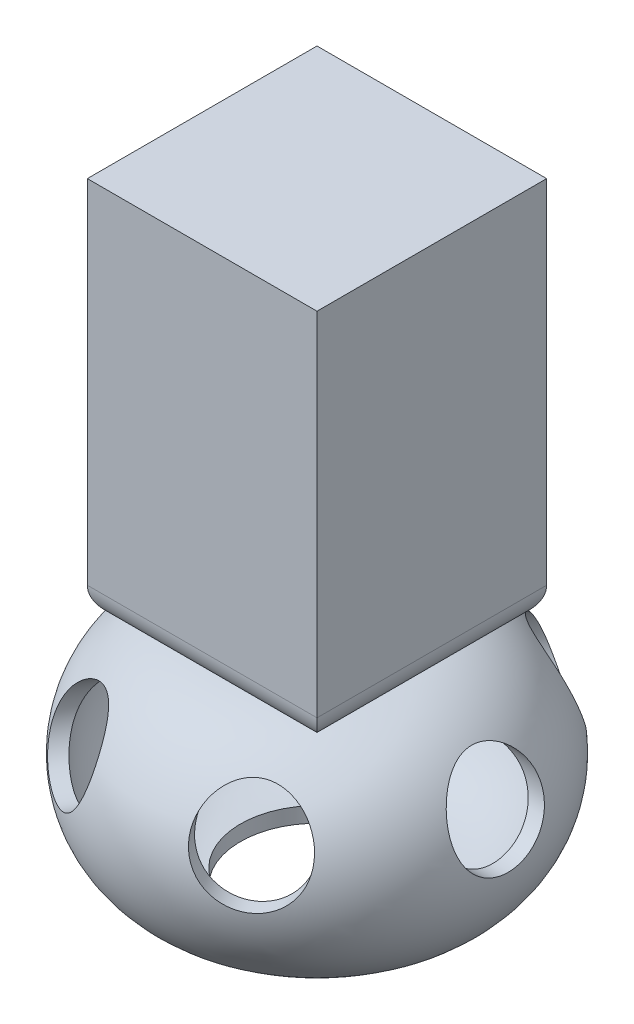
SolidWorks part; units mm, degrees
material "PLA"
ref_plane "Front Plane" through (0, 0, 0) normal (0, 0, 1) x (1, 0, 0)
ref_plane "Top Plane" through (0, 0, 0) normal (0, 1, 0) x (1, 0, 0)
ref_plane "Right Plane" through (0, 0, 0) normal (1, 0, 0) x (0, 0, -1)
sketch "Sketch1" plane through (0, 0, 0) normal (0, 1, 0) x (1, 0, 0)
  line L1 (-2.5, 10) -> (2.5, 10) construction
  line L2 (-2.5, 10) -> (-2.5, -10) construction
  line L3 (-2.5, -10) -> (2.5, -10) construction
  line L4 (2.5, 10) -> (2.5, -10) construction
  line L5 (-2.5, 10) -> (2.5, -10) construction
  line L6 (-2.5, -10) -> (2.5, 10) construction
  point P0 (0, 0)
  dimension "D1" = 5
  dimension "D2" = 20
ref_axis "Axis1" through (0, 0, 0) along (0, 1, 0)
sketch "Sketch2" plane through (0, 0, 0) normal (0, 0, 1) x (1, 0, 0)
  line L0 (0, 0) -> (2.5, 0) construction
  line L1 (2.5, 7.5) -> (0, 7.5)
  line L2 (0, 0) -> (0, 7.4834) construction
  line L3 (2.5, 7) -> (0, 7)
  line L4 (2.5, 0.5) -> (2.5, 0)
  line L5 (0, 7) -> (0, 7.5)
  arc A0 (2.5, 0) -> (2.5, 7.5) centre (2.5, 3.75) ccw
  arc A1 (2.5, 0.5) -> (2.5, 7) centre (2.5, 3.75) ccw
  dimension "D2" = 0.5
  dimension "D1" = 7.5
revolve "Revolve1" add sketch "Sketch2" angle 360 about axis through (0, 0, 0) along (0, 1, 0)
sketch "Sketch3" plane through (0, 0, 0) normal (1, 0, 0) x (0, 0, -1)
  line L0 (0, 0) -> (0, 7.4834) construction
  circle A0 centre (0, 5) radius 1.5
  point P4 (0, 0)
  point P5 (0, 3.5986)
  point P6 (0, 6.2275)
  dimension "D1" = 3
  dimension "D2" = 5
extrude "Cut-Extrude1" cut sketch "Sketch3" against normal through all both and the other way through all
pattern_circular "CirPattern1" count 6 over 360 about axis through (0, 0, 0) along (0, 1, 0) of "Cut-Extrude1"
sketch "Sketch4" plane through (0, 7.5, 0) normal (0, 1, 0) x (1, 0, 0)
  line L1 (-3.75, 3.75) -> (3.75, 3.75)
  line L2 (-3.75, 3.75) -> (-3.75, -3.75)
  line L3 (-3.75, -3.75) -> (3.75, -3.75)
  line L4 (3.75, 3.75) -> (3.75, -3.75)
  line L5 (-3.75, 3.75) -> (3.75, -3.75) construction
  line L6 (-3.75, -3.75) -> (3.75, 3.75) construction
  point P0 (0, 0)
  dimension "D1" = 7.5
  dimension "D2" = 7.5
extrude "Boss-Extrude2" add sketch "Sketch4" along normal blind 12.5
fillet "Fillet1" radius 1 4 edges at (-3.75, 7.5, 0) (0, 7.5, -3.75) (3.75, 7.5, 0) (0, 7.5, 3.75)
